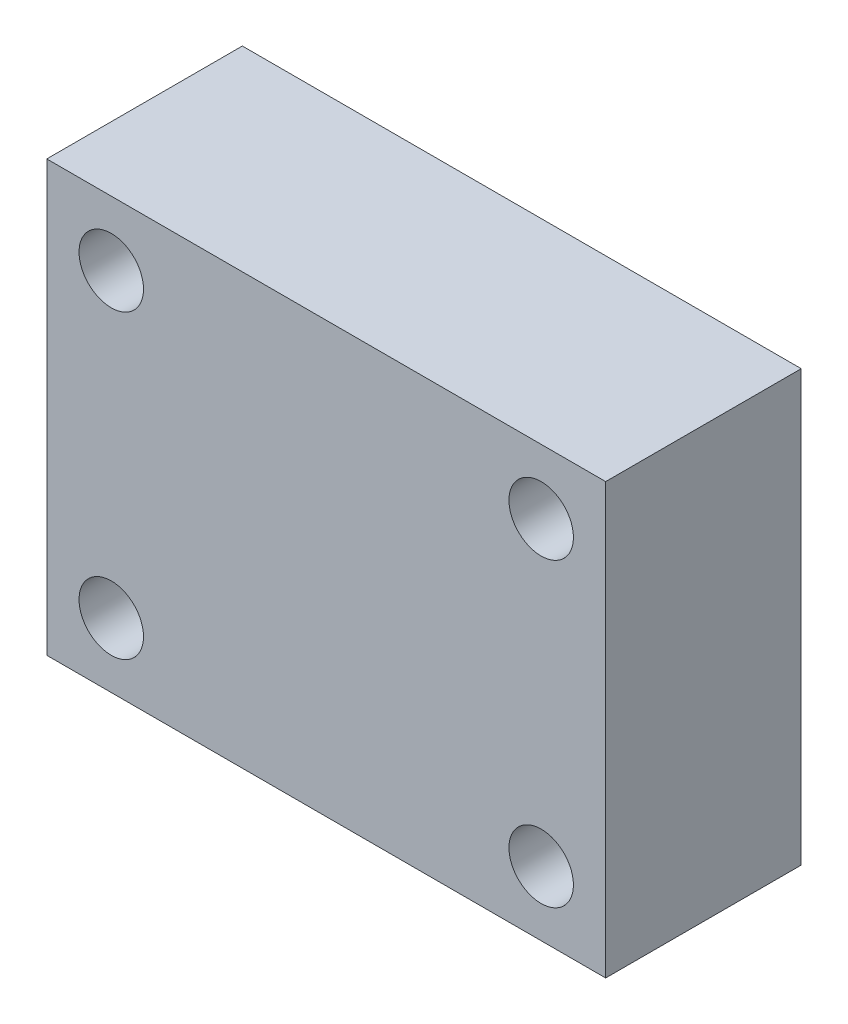
SolidWorks part; units mm, degrees
ref_plane "Front Plane" through (0, 0, 0) normal (0, 0, 1) x (1, 0, 0)
ref_plane "Top Plane" through (0, 0, 0) normal (0, 1, 0) x (1, 0, 0)
ref_plane "Right Plane" through (0, 0, 0) normal (1, 0, 0) x (0, 0, -1)
sketch "Sketch1" plane through (0, 0, 0) normal (0, 0, 1) x (1, 0, 0)
  line L1 (0, 0) -> (52, 0)
  line L2 (0, 0) -> (0, -40)
  line L3 (0, -40) -> (52, -40)
  line L4 (52, 0) -> (52, -40)
  circle A0 centre (6, -6) radius 3
  circle A1 centre (46, -6) radius 3
  circle A2 centre (6, -34) radius 3
  circle A3 centre (46, -34) radius 3
  dimension "D3" = 6
  dimension "D11" = 6
  dimension "D12" = 6
  dimension "D13" = 6
  dimension "D14" = 6
  dimension "D1" = 40
  dimension "D2" = 52
  dimension "D4" = 6
  dimension "D5" = 6
  dimension "D6" = 6
  dimension "D7" = 6
  dimension "D8" = 6
  dimension "D9" = 6
  dimension "D10" = 6
extrude "Boss-Extrude1" add sketch "Sketch1" along normal blind 18.1949
